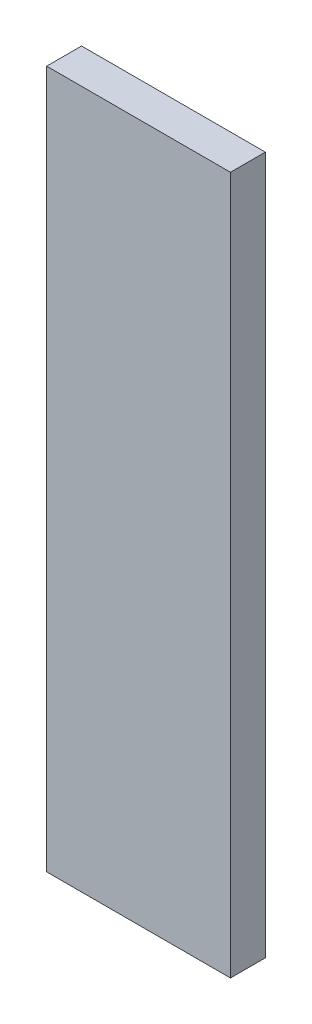
SolidWorks part; units mm, degrees
material "Pin"
ref_plane "Front" through (0, 0, 0) normal (0, 0, 1) x (1, 0, 0)
ref_plane "Top" through (0, 0, 0) normal (0, 1, 0) x (1, 0, 0)
ref_plane "Right" through (0, 0, 0) normal (1, 0, 0) x (0, 0, -1)
sketch "Esquisse1" plane through (0, 0, 0) normal (0, 0, 1) x (1, 0, 0)
  line L1 (-16.7259, 63.5) -> (16.7259, 63.5)
  line L2 (-16.7259, 63.5) -> (-16.7259, -63.5)
  line L3 (-16.7259, -63.5) -> (16.7259, -63.5)
  line L4 (16.7259, 63.5) -> (16.7259, -63.5)
  line L5 (-16.7259, 63.5) -> (16.7259, -63.5) construction
  line L6 (-16.7259, -63.5) -> (16.7259, 63.5) construction
  point P1 (0, 0)
  dimension "D1" = 127
  dimension "D2" = 33.4518
extrude "Boss.-Extru.1" add sketch "Esquisse1" along normal blind 6.35
